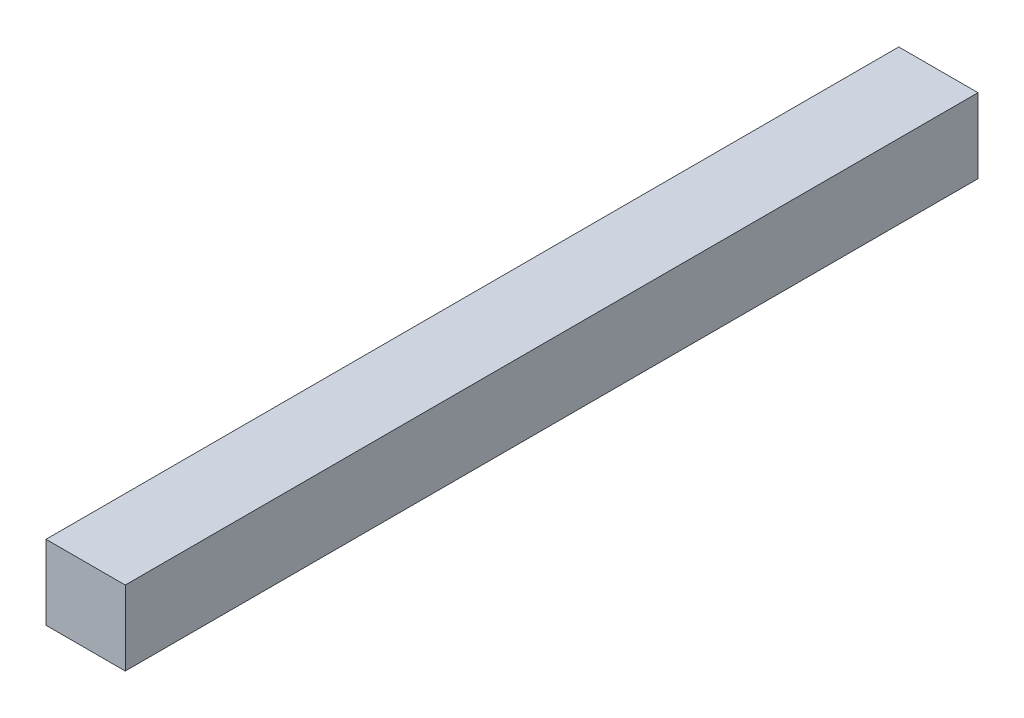
SolidWorks part; units mm, degrees
ref_plane "Front Plane" through (0, 0, 0) normal (0, 0, 1) x (1, 0, 0)
ref_plane "Top Plane" through (0, 0, 0) normal (0, 1, 0) x (1, 0, 0)
ref_plane "Right Plane" through (0, 0, 0) normal (1, 0, 0) x (0, 0, -1)
sketch "Sketch1" plane through (0, 0, 0) normal (0, 0, 1) x (1, 0, 0)
  line L1 (-26.6667, 25.1515) -> (23.3333, 25.1515)
  line L2 (-26.6667, 25.1515) -> (-26.6667, -21.8485)
  line L3 (-26.6667, -21.8485) -> (23.3333, -21.8485)
  line L4 (23.3333, 25.1515) -> (23.3333, -21.8485)
  dimension "D1" = 50
  dimension "D2" = 47
extrude "Boss-Extrude1" add sketch "Sketch1" along normal blind 538
